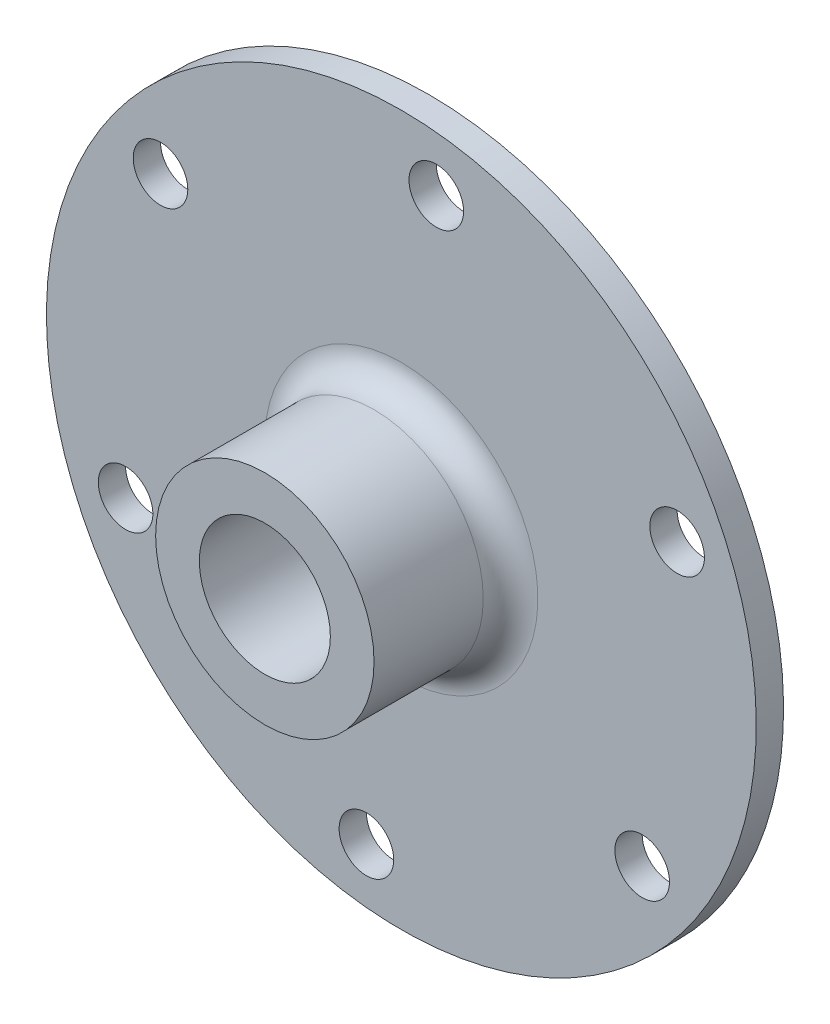
SolidWorks part; units mm, degrees
material "AISI 1020"
ref_plane "Front Plane" through (0, 0, 0) normal (0, 0, 1) x (1, 0, 0)
ref_plane "Top Plane" through (0, 0, 0) normal (0, 1, 0) x (1, 0, 0)
ref_plane "Right Plane" through (0, 0, 0) normal (1, 0, 0) x (0, 0, -1)
sketch "Sketch2" plane through (0, 0, 0) normal (1, 0, 0) x (0, 0, -1)
  line L2 (0, 0) -> (0, 41.275)
  line L3 (0, 41.275) -> (-3.175, 41.275)
  line L4 (-3.175, 12.7) -> (-3.175, 41.275)
  line L5 (0, 0) -> (-19.05, 0)
  line L7 (-3.175, 12.7) -> (-19.05, 12.7)
  line L8 (-19.05, 0) -> (-19.05, 12.7)
  dimension "D1" = 19.05
  dimension "D2" = 41.275
  dimension "D3" = 3.175
  dimension "D4" = 12.7
revolve "Revolve1" add sketch "Sketch2" angle 360 about L5
sketch "Sketch3" plane through (0, 0, 19.05) normal (0, 0, 1) x (1, 0, 0)
  circle A0 centre (0, 0) radius 7.62
  circle A1 centre (0, 0) radius 34.925 construction
  circle A2 centre (-28.0086, 20.8632) radius 3.175
  dimension "D1" = 15.24
extrude "Cut-Extrude1" cut sketch "Sketch3" against normal through all
pattern_circular "CirPattern1" count 6 over 360 about axis through (0, 0, 0) along (0, 0, 1) of "Cut-Extrude1"
fillet "Fillet1" radius 3.175 1 edges at (0, 12.7, 3.175)
other "DeleteFace2" [suppressed]
